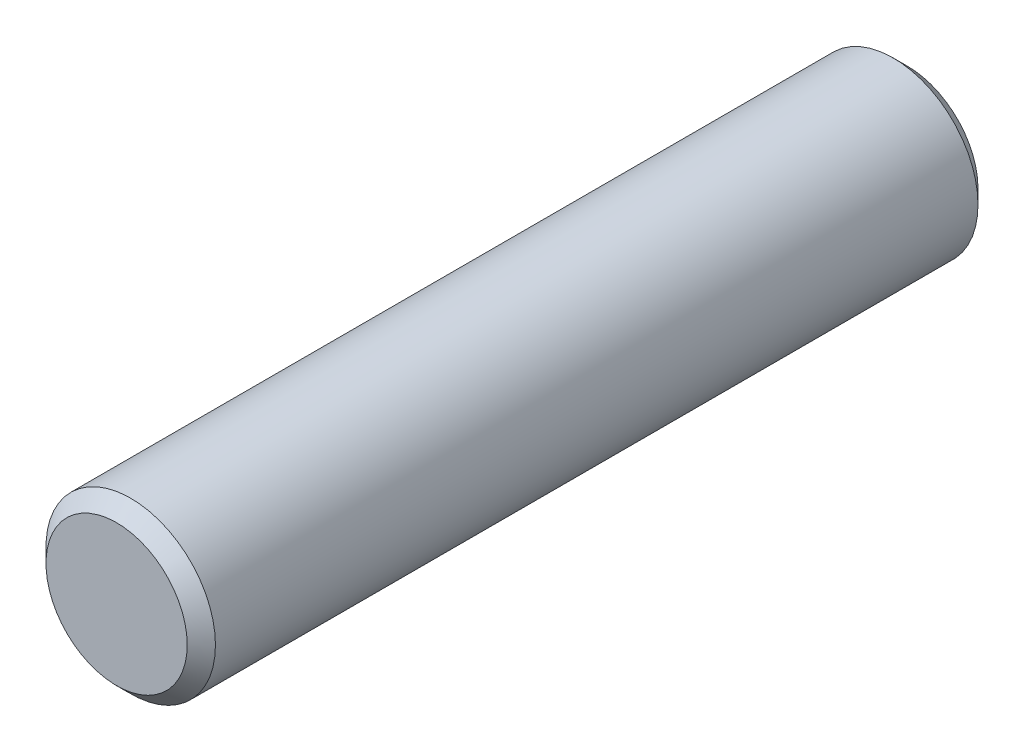
SolidWorks part; units mm, degrees
ref_plane "Front Plane" through (0, 0, 0) normal (0, 0, 1) x (1, 0, 0)
ref_plane "Top Plane" through (0, 0, 0) normal (0, 1, 0) x (1, 0, 0)
ref_plane "Right Plane" through (0, 0, 0) normal (1, 0, 0) x (0, 0, -1)
sketch "Sketch2" plane through (0, 0, 0) normal (0, 0, 1) x (1, 0, 0)
  circle A0 centre (0, 0) radius 19.05
  dimension "D1" = 38.1
extrude "Boss-Extrude1" add sketch "Sketch2" along normal mid plane 177.8
chamfer "Chamfer1" distance 3.175 angle 45 2 edges at (19.05, 0, -88.9) (19.05, 0, 88.9)
